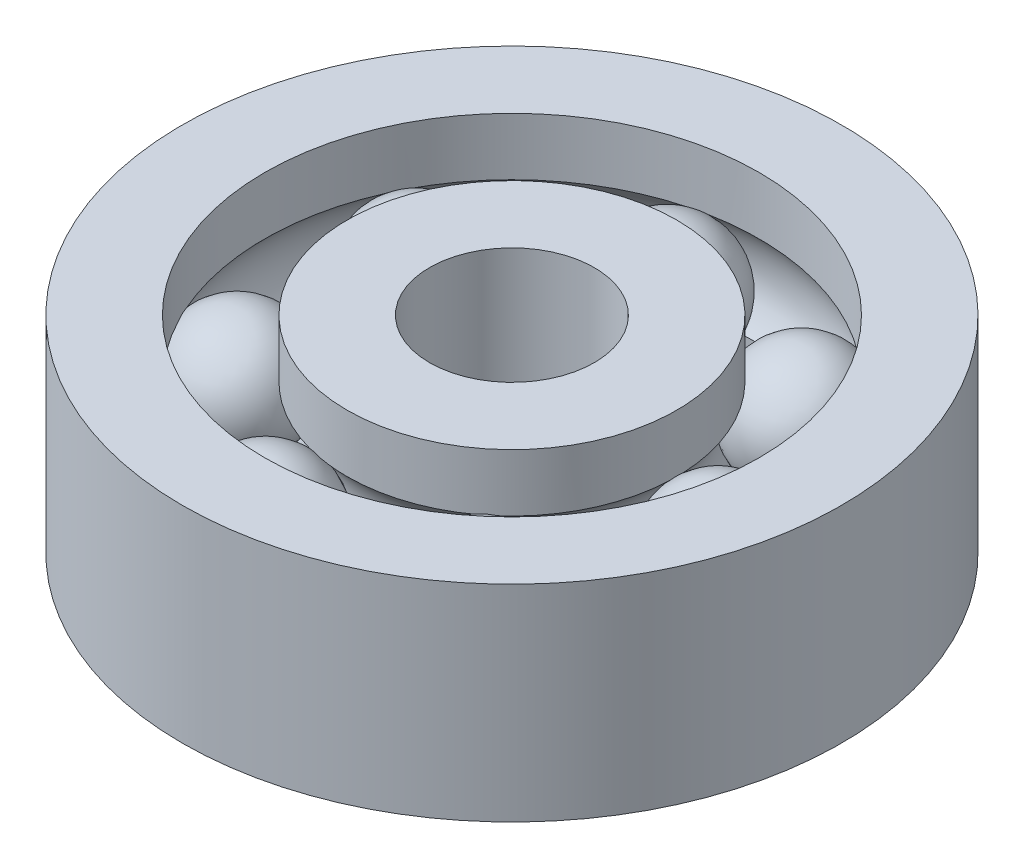
SolidWorks part; units mm, degrees
material "Gcr15"
ref_plane "前视基准面" through (0, 0, 0) normal (0, 0, 1) x (1, 0, 0)
ref_plane "上视基准面" through (0, 0, 0) normal (0, 1, 0) x (1, 0, 0)
ref_plane "右视基准面" through (0, 0, 0) normal (1, 0, 0) x (0, 0, -1)
sketch "草图2" plane through (0, 0, 0) normal (0, 0, 1) x (1, 0, 0)
  line L0 (0, 3.6964) -> (0, 0) construction
  line L2 (4, 5) -> (2, 5)
  line L3 (2, 5) -> (2, 0)
  line L4 (2, 0) -> (4, 0)
  line L6 (5, -0.2392) -> (5, 2.2016) construction
  line L7 (4, 5) -> (4, 3.6046)
  line L8 (4, 0) -> (4, 1.3954)
  line L9 (2.8829, 2.5) -> (-1.7643, 2.5) construction
  arc A0 (4, 3.6046) -> (4, 1.3954) centre (5, 2.5) ccw
  dimension "D5" = 2.5
  dimension "D6" = 5
  dimension "D4" = 2.98
  dimension "D1" = 4
  dimension "D3" = 5
  dimension "D2" = 2
revolve "旋转2" add sketch "草图2" angle 360 about L0
sketch "草图4" plane through (0, 0, 0) normal (0, 0, 1) x (1, 0, 0)
  line L0 (6, 3.6046) -> (6, 5)
  line L1 (6, 5) -> (8, 5)
  line L2 (8, 5) -> (8, 0)
  line L3 (8, 0) -> (6, 0)
  line L4 (6, 0) -> (6, 1.3954)
  line L5 (0, 2.6227) -> (0, -0.5389) construction
  line L6 (5, 2.2519) -> (5, -0.4511) construction
  line L7 (-2.6124, 2.5) -> (3.1617, 2.5) construction
  arc A0 (6, 1.3954) -> (6, 3.6046) centre (5, 2.5) ccw
  dimension "D1" = 2.98
  dimension "D2" = 5
  dimension "D3" = 16
  dimension "D4" = 2
  dimension "D5" = 2.5
  dimension "D6" = 5
revolve "旋转3" add sketch "草图4" angle 360 about L5
sketch "草图1" plane through (0, 0, 0) normal (0, 0, 1) x (1, 0, 0)
  line L0 (0, 0) -> (0, 3.6964) construction
  line L1 (5, 4) -> (5, 1)
  arc A0 (5, 1) -> (5, 4) centre (5, 2.5) ccw
  dimension "D1" = 3
  dimension "D2" = 2.5
  dimension "D3" = 10
revolve "旋转4" add sketch "草图1" angle 360 about L1
pattern_circular "阵列(圆周)1" count 7 over 360 about axis through (0, 0, 0) along (0, 1, 0) of "旋转4"
fillet "圆角1" [suppressed] radius 0.1
equation "\"D5@草图4\"=0.5*\"D2@草图4\""
equation "\"D5@草图2\"=0.5*\"D3@草图2\""
equation "\"D6@草图4\"=(\"D3@草图4\"+\"D1@草图2\")/4"
equation "\"D6@草图2\"=\"D6@草图4\""
equation "\"D4@草图4\"=(\"D3@草图4\"-\"D1@草图2\")/6"
equation "\"D2@草图2\"=\"D4@草图4\""
equation "\"D1@草图1\"=(\"D3@草图4\"-\"D1@草图2\")/4"
equation "\"D1@草图4\"=\"D1@草图1\"-0.02"
equation "\"D4@草图2\"=\"D1@草图4\""
equation "\"D2@草图4\"=\"D3@草图2\""
equation "\"D2@草图1\"=0.5*\"D2@草图4\""
equation "\"D3@草图1\"=(\"D1@草图2\"+\"D3@草图4\")/2"
equation "\"D1@阵列(圆周)1\"=0.7*(3.1415*\"D3@草图1\")/\"D1@草图1\""
